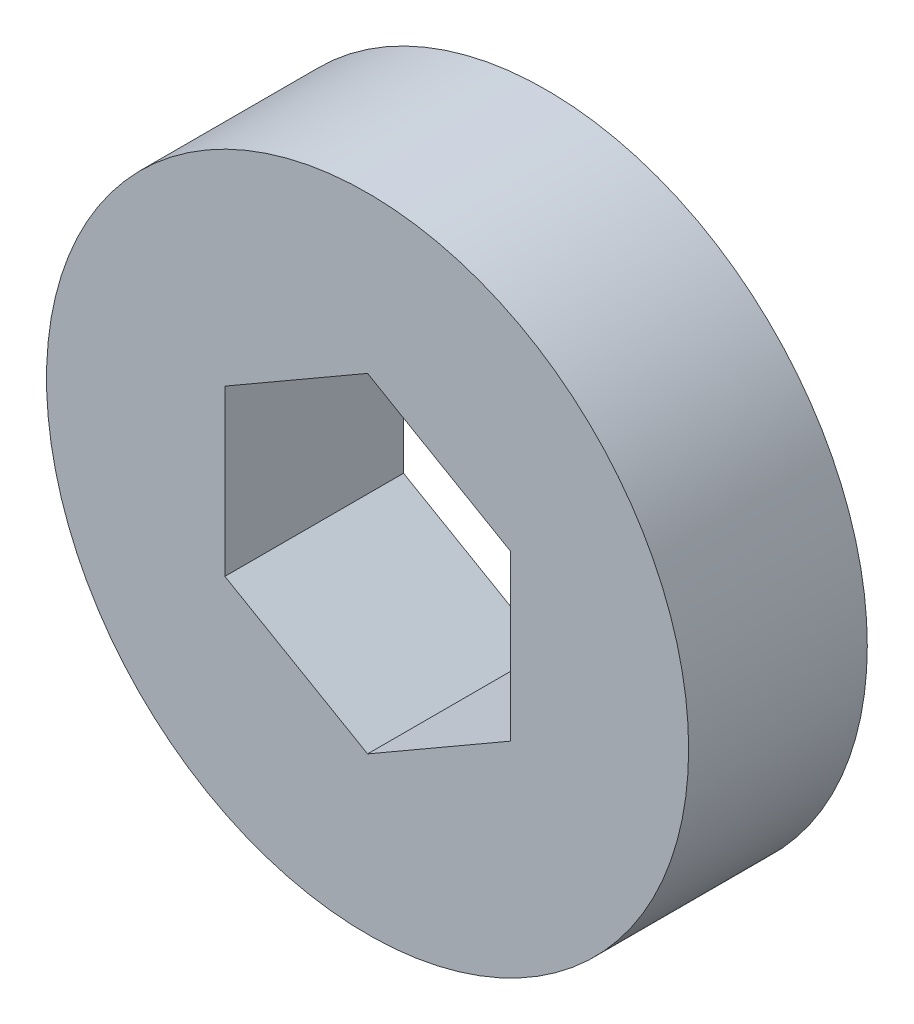
SolidWorks part; units mm, degrees
ref_plane "Front Plane" through (0, 0, 0) normal (1, 0, 0) x (0, 1, 0)
ref_plane "Top Plane" through (0, 0, 0) normal (0, 0, 1) x (0, 1, 0)
ref_plane "Right Plane" through (0, 0, 0) normal (0, 1, 0) x (-1, 0, 0)
sketch "Sketch1" plane through (0, 0, 0) normal (0, 0, 1) x (0, 1, 0)
  line L1 (3.6662, 6.35) -> (-3.6662, 6.35)
  line L2 (-3.6662, 6.35) -> (-7.3323, 0)
  line L3 (-7.3323, 0) -> (-3.6662, -6.35)
  line L4 (-3.6662, -6.35) -> (3.6662, -6.35)
  line L5 (3.6662, -6.35) -> (7.3323, 0)
  line L6 (7.3323, 0) -> (3.6662, 6.35)
  circle A0 centre (0, 0) radius 6.35 construction
  circle A1 centre (0, 0) radius 14.2875
  dimension "D2" = 28.575
  dimension "D1" = 12.7
extrude "Boss-Extrude1" add sketch "Sketch1" along normal blind 7.9502
